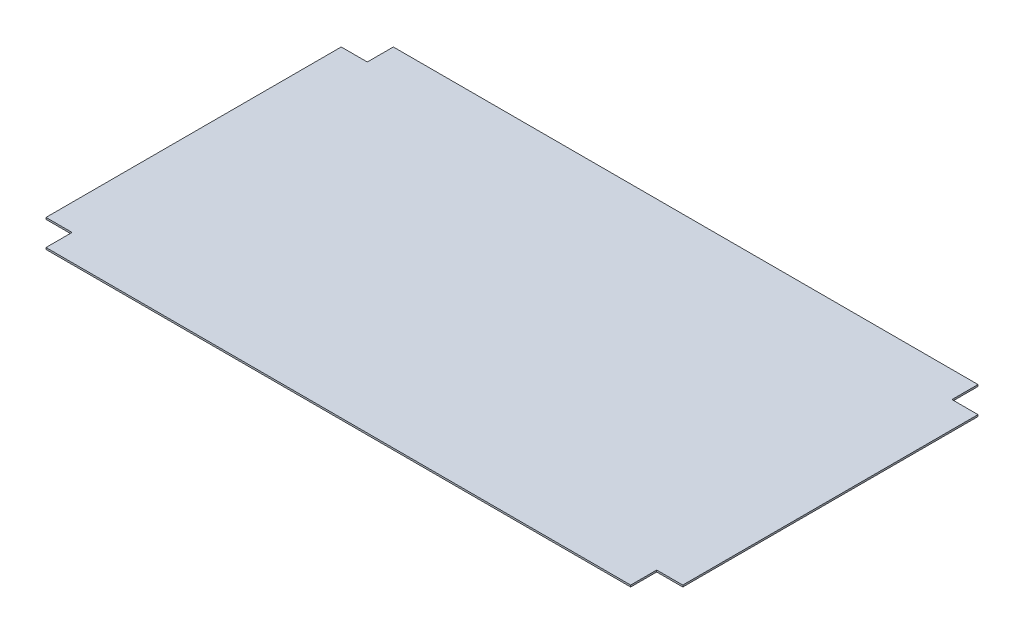
SolidWorks part; units mm, degrees
material "Nailon 101"
ref_plane "Alzado" through (0, 0, 0) normal (0, 0, 1) x (1, 0, 0)
ref_plane "Planta" through (0, 0, 0) normal (0, 1, 0) x (1, 0, 0)
ref_plane "Vista lateral" through (0, 0, 0) normal (1, 0, 0) x (0, 0, -1)
sketch "Croquis1" plane through (0, 0, 0) normal (0, 1, 0) x (1, 0, 0)
  line L1 (550, -300) -> (-550, -300)
  line L2 (550, -300) -> (550, 300)
  line L3 (550, 300) -> (-550, 300)
  line L4 (-550, -300) -> (-550, 300)
  line L5 (550, -300) -> (-550, 300) construction
  line L6 (550, 300) -> (-550, -300) construction
  point P0 (0, 0)
  dimension "D1" = 600
  dimension "D2" = 1100
extrude "Extruir1" add sketch "Croquis1" along normal blind 3
sketch "Croquis2" plane through (0, 3, 0) normal (0, 1, 0) x (1, 0, 0)
  line L0 (0, 300) -> (0, 0) construction
  line L1 (-550, 300) -> (-505, 300)
  line L2 (-550, 300) -> (-550, 255)
  line L3 (-550, 255) -> (-505, 255)
  line L4 (-505, 300) -> (-505, 255)
  line L5 (550, 300) -> (-550, 300) construction
  line L6 (0, 0) -> (550, 0) construction
  line L7 (550, -300) -> (550, 300) construction
  line L8 (505, 300) -> (505, 255)
  line L9 (550, 255) -> (505, 255)
  line L10 (550, 300) -> (550, 255)
  line L11 (550, 300) -> (505, 300)
  line L12 (-505, -300) -> (-505, -255)
  line L13 (-550, -255) -> (-505, -255)
  line L14 (-550, -300) -> (-550, -255)
  line L15 (-550, -300) -> (-505, -300)
  line L16 (550, -300) -> (505, -300)
  line L17 (550, -300) -> (550, -255)
  line L18 (550, -255) -> (505, -255)
  line L19 (505, -300) -> (505, -255)
  dimension "D1" = 45
  dimension "D2" = 45
extrude "Extruir2" cut sketch "Croquis2" against normal blind 3
